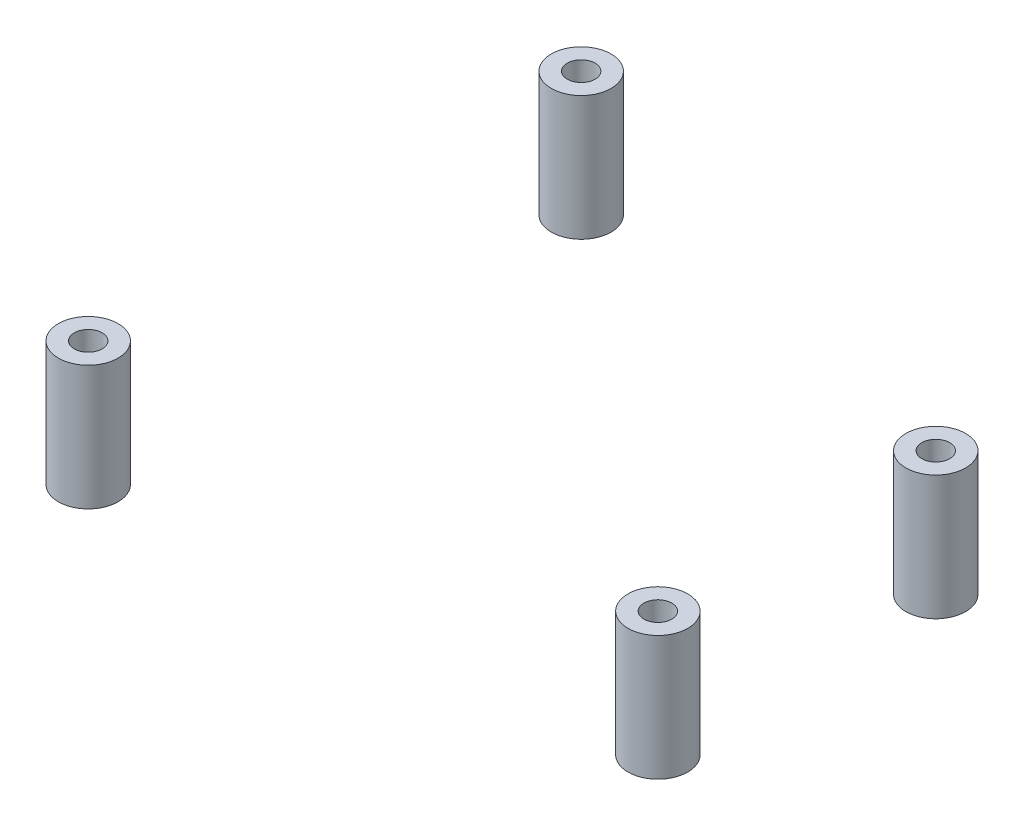
SolidWorks part; units mm, degrees
ref_plane "Front Plane" through (0, 0, 0) normal (0, 0, 1) x (1, 0, 0)
ref_plane "Top Plane" through (0, 0, 0) normal (0, 1, 0) x (1, 0, 0)
ref_plane "Right Plane" through (0, 0, 0) normal (1, 0, 0) x (0, 0, -1)
sketch "Sketch1" plane through (0, 0, 0) normal (0, 1, 0) x (1, 0, 0)
  line L0 (-35.9621, -39.8108) -> (84.0379, -39.8108) construction
  line L1 (-26.2621, 15.9892) -> (42.3379, 15.9892)
  line L2 (-26.2621, 15.9892) -> (-26.2621, -37.3108)
  line L3 (-26.2621, -37.3108) -> (42.3379, -37.3108)
  line L4 (42.3379, 15.9892) -> (42.3379, -37.3108)
  line L5 (-60.9621, 38.4392) -> (-60.9621, -9.8608) construction
  circle A0 centre (-12.2621, -34.8108) radius 3
  circle A1 centre (-10.9621, 13.3892) radius 3
  circle A2 centre (39.8379, -1.8108) radius 3
  circle A3 centre (39.8379, -29.7108) radius 3
  point P12 (0, 0)
  point P13 (0, 0)
  point P14 (0, 0)
  point P15 (0, 0)
  point P16 (0, 0)
  point P17 (0, 0)
  point P18 (0, 0)
  dimension "D3" = 6
  dimension "D1" = 53.3
  dimension "D2" = 68.6
  dimension "D4" = 2.5
  dimension "D5" = 14
  dimension "D6" = 50.8
  dimension "D7" = 27.9
  dimension "D8" = 15.2
  dimension "D9" = 48.2
  dimension "D10" = 1.3
  dimension "D11" = 5
  dimension "D12" = 50
extrude "Boss-Extrude1" add sketch "Sketch1" along normal blind 12.5 contours A1 | A0 | A3 | A2
sketch "Sketch2" plane through (0, 12.5, 0) normal (0, 1, 0) x (1, 0, 0)
  circle A0 centre (-10.9621, 13.3892) radius 1.4
  circle A1 centre (39.8379, -1.8108) radius 1.4
  circle A2 centre (39.8379, -29.7108) radius 1.4
  circle A3 centre (-12.2621, -34.8108) radius 1.4
  dimension "D1" = 2.8
extrude "Cut-Extrude1" cut sketch "Sketch2" against normal blind 10
